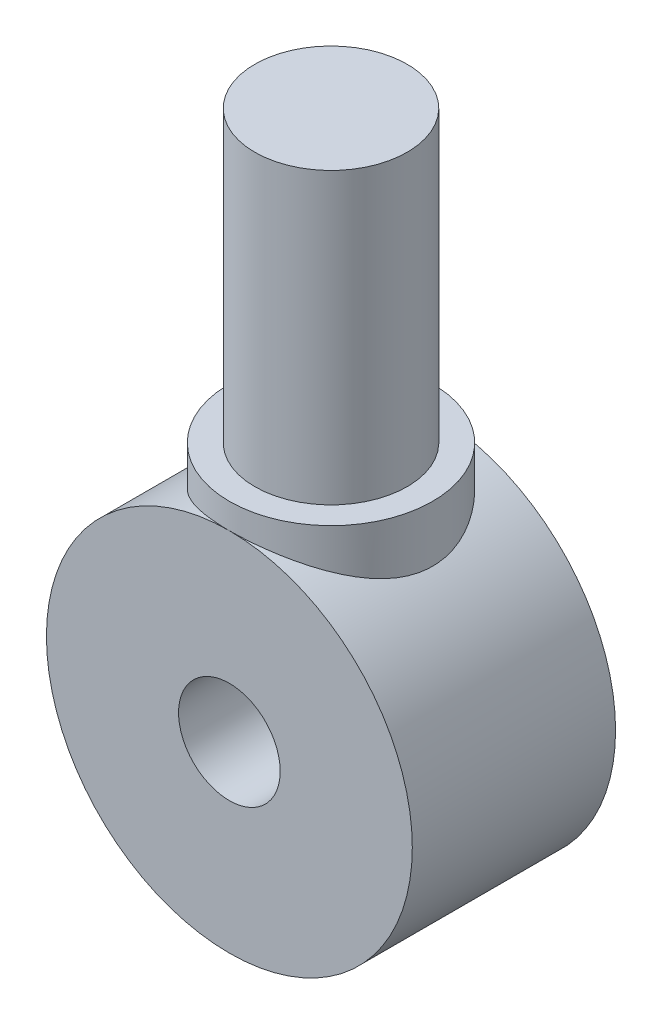
SolidWorks part; units mm, degrees
ref_plane "Спереди" through (0, 0, 0) normal (0, 0, 1) x (1, 0, 0)
ref_plane "Сверху" through (0, 0, 0) normal (0, 1, 0) x (1, 0, 0)
ref_plane "Справа" through (0, 0, 0) normal (1, 0, 0) x (0, 0, -1)
ref_plane "Плоскость1" through (0, 14, 0) normal (0, 1, 0) x (-1, 0, 0)
sketch "Эскиз1" plane through (0, 0, 0) normal (0, 0, 1) x (1, 0, 0)
  circle A0 centre (0, 0) radius 5
  circle A1 centre (0, 0) radius 18
extrude "Вытянуть1" add sketch "Эскиз1" along normal blind 20
sketch "Эскиз2" plane through (0, 14, 0) normal (0, 1, 0) x (1, 0, 0)
  line L0 (0, 0) -> (0, 4.236) construction
  line L5 (-18, -10) -> (-24.6281, -10) construction
  circle A0 centre (0, -10) radius 10
extrude "Вытянуть2" add sketch "Эскиз2" along normal blind 35
sketch "Эскиз4" plane through (0, 49, 0) normal (0, 1, 0) x (1, 0, 0)
  circle A0 centre (0, -10) radius 15
  circle A1 centre (0, -10) radius 7.5
extrude "Вытянуть3" cut sketch "Эскиз4" against normal blind 28.5
